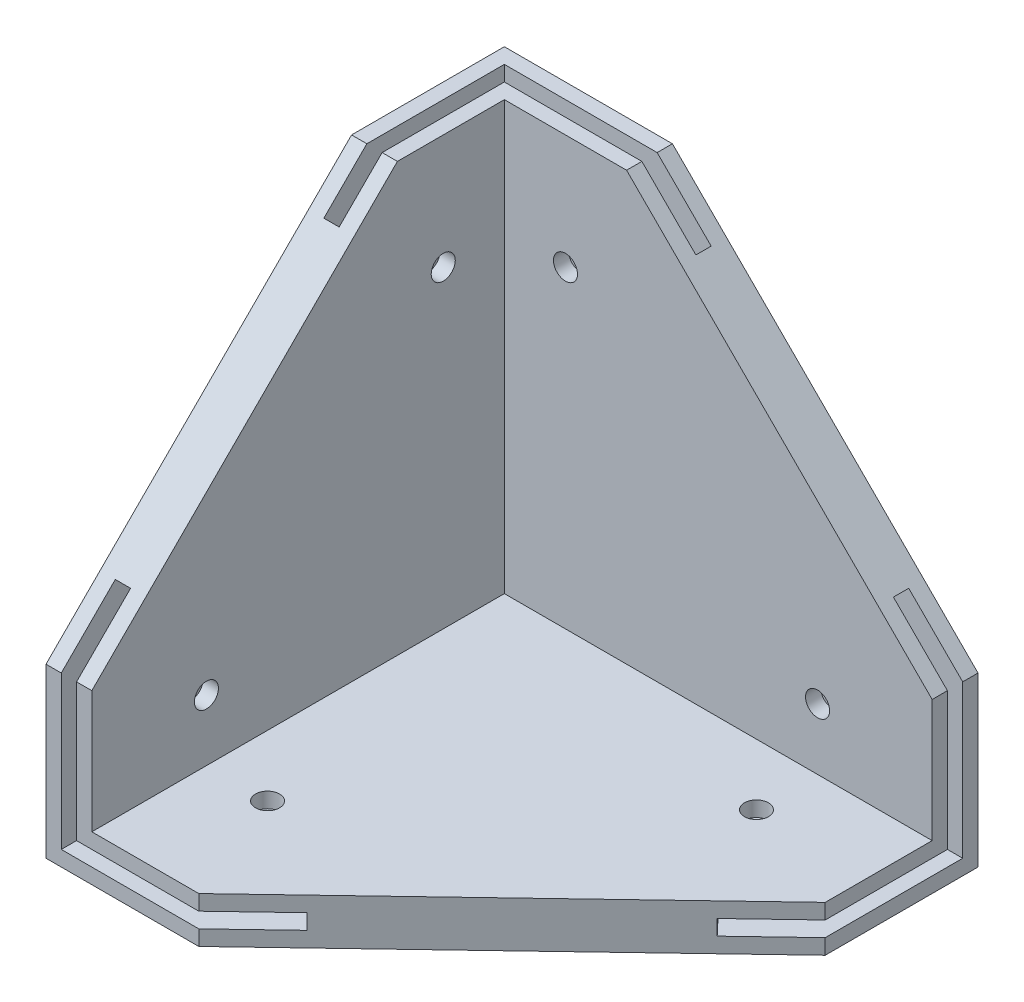
SolidWorks part; units mm, degrees
ref_plane "Front Plane" through (0, 0, 0) normal (0, 0, 1) x (1, 0, 0)
ref_plane "Top Plane" through (0, 0, 0) normal (0, 1, 0) x (1, 0, 0)
ref_plane "Right Plane" through (0, 0, 0) normal (1, 0, 0) x (0, 0, -1)
sketch "Sketch1" plane through (0, 0, 0) normal (0, 0, 1) x (1, 0, 0)
  line L0 (0, 76.2) -> (0, 0)
  line L1 (0, 0) -> (76.2, 0)
  line L2 (76.2, 0) -> (76.2, 25.4)
  line L3 (76.2, 25.4) -> (25.4, 76.2)
  line L4 (25.4, 76.2) -> (0, 76.2)
  dimension "D1" = 76.2
  dimension "D2" = 76.2
  dimension "D3" = 25.4
  dimension "D4" = 25.4
extrude "Boss-Extrude1" add sketch "Sketch1" along normal blind 2.54
sketch "Sketch3" plane through (0, 0, 0) normal (-1, 0, 0) x (0, 0, 1)
  line L0 (0, 76.2) -> (25.4, 76.2)
  line L2 (0, 76.2) -> (0, 0)
  line L3 (0, 0) -> (76.2, 0)
  line L4 (76.2, 0) -> (76.2, 25.4)
  line L6 (25.4, 76.2) -> (76.2, 25.4)
  dimension "D1" = 25.4
  dimension "D2" = 25.4
  dimension "D3" = 76.2
extrude "Boss-Extrude2" add sketch "Sketch3" along normal blind 2.54
sketch "Sketch5" plane through (0, 0, 0) normal (0, -1, 0) x (1, 0, 0)
  line L0 (-2.54, 76.2) -> (-2.54, 0)
  line L1 (-2.54, 0) -> (-2.54, 76.2) construction
  line L2 (-2.54, 0) -> (76.2, 0)
  line L3 (76.2, 0) -> (76.2, 25.4)
  line L4 (76.2, 25.4) -> (22.86, 76.2)
  line L5 (22.86, 76.2) -> (-2.54, 76.2)
  line L6 (-2.54, 76.2) -> (0, 76.2) construction
  dimension "D1" = 25.4
  dimension "D2" = 25.4
extrude "Boss-Extrude3" add sketch "Sketch5" along normal blind 2.54
sketch "Sketch6" plane through (0, 0, 0) normal (0, 0, 1) x (1, 0, 0)
  line L0 (22.86, 0) -> (0, 0) construction
  line L1 (2.54, 0) -> (5.08, 0)
  line L2 (2.54, 0) -> (2.54, 76.2)
  line L3 (2.54, 76.2) -> (5.08, 76.2)
  line L4 (5.08, 0) -> (5.08, 76.2)
  line L5 (25.4, 76.2) -> (0, 76.2) construction
  line L6 (0, 76.2) -> (0, 0) construction
  dimension "D1" = 2.54
  dimension "D2" = 2.54
extrude "Boss-Extrude4" add sketch "Sketch6" along direction (0, 0, -1) on the side of the normal blind 76.2
sketch "Sketch7" plane through (0, 0, 0) normal (1, 0, 0) x (0, 0, -1)
  line L0 (-25.4, 76.2) -> (-76.2, 25.4)
  line L1 (-76.2, 25.4) -> (-76.2, 76.2)
  line L2 (-76.2, 76.2) -> (-25.4, 76.2)
extrude "Cut-Extrude1" cut sketch "Sketch7" along normal up to next
sketch "Sketch8" plane through (0, 0, 0) normal (1, 0, 0) x (0, 0, -1)
  line L0 (-25.4, 76.2) -> (-2.54, 76.2) construction
  line L1 (-7.62, 76.2) -> (-5.08, 76.2)
  line L2 (-7.62, 76.2) -> (-7.62, -2.54)
  line L3 (-7.62, -2.54) -> (-5.08, -2.54)
  line L4 (-5.08, 76.2) -> (-5.08, -2.54)
  line L5 (0, -2.54) -> (-25.4, -2.54) construction
  line L6 (-2.54, 76.2) -> (-2.54, 0) construction
  dimension "D1" = 2.54
  dimension "D2" = 2.54
extrude "Boss-Extrude5" add sketch "Sketch8" along normal blind 76.2
sketch "Sketch9" plane through (0, 0, 0) normal (0, 0, 1) x (1, 0, 0)
  line L0 (76.2, 25.4) -> (25.4, 76.2)
  line L1 (25.4, 76.2) -> (76.2, 76.2)
  line L2 (76.2, 76.2) -> (76.2, 25.4)
extrude "Cut-Extrude2" cut sketch "Sketch9" along normal up to next
sketch "Sketch10" plane through (0, 0, 0) normal (0, 0, 1) x (1, 0, 0)
  line L0 (-2.54, -2.54) -> (-2.54, 25.4) construction
  line L1 (-2.54, 2.54) -> (76.2, 2.54)
  line L2 (-2.54, 2.54) -> (-2.54, 5.08)
  line L3 (-2.54, 5.08) -> (76.2, 5.08)
  line L4 (76.2, 2.54) -> (76.2, 5.08)
  line L5 (76.2, 25.4) -> (76.2, 0) construction
  line L6 (5.08, 0) -> (76.2, 0) construction
  dimension "D1" = 2.54
  dimension "D2" = 2.54
extrude "Boss-Extrude6" add sketch "Sketch10" along normal blind 76.2
sketch "Sketch11" plane through (0, 0, 0) normal (0, 1, 0) x (1, 0, 0)
  line L0 (22.86, -76.2) -> (76.2, -25.4)
  line L1 (76.2, -25.4) -> (76.2, -76.2)
  line L2 (76.2, -76.2) -> (22.86, -76.2)
extrude "Cut-Extrude3" cut sketch "Sketch11" along normal up to next
sketch "Sketch12" plane through (0, 0, 0) normal (1, 0, 0) x (0, 0, -1)
  line L0 (-5.08, 5.08) -> (-5.08, 2.54)
  line L1 (-5.08, 2.54) -> (-7.62, 2.54)
  line L2 (-7.62, 2.54) -> (-7.62, 0)
  line L3 (-7.62, 2.54) -> (-7.62, 0) construction
  line L4 (-7.62, 0) -> (-2.54, 0)
  line L5 (-2.54, 0) -> (-2.54, 5.08)
  line L6 (-2.54, 5.08) -> (-5.08, 5.08)
extrude "Cut-Extrude5" cut sketch "Sketch12" along normal through all
sketch "Sketch13" plane through (0, 0, 0) normal (0, 1, 0) x (1, 0, 0)
  line L0 (0, -2.54) -> (0, -7.62)
  line L1 (0, -7.62) -> (2.54, -7.62)
  line L2 (2.54, -7.62) -> (2.54, -5.08)
  line L3 (2.54, -5.08) -> (2.54, -2.54) construction
  line L4 (2.54, -5.08) -> (5.08, -5.08)
  line L5 (5.08, -5.08) -> (5.08, -2.54)
  line L6 (5.08, -2.54) -> (0, -2.54)
extrude "Cut-Extrude6" cut sketch "Sketch13" along normal through all
sketch "Sketch15" plane through (0, 0, 2.54) normal (0, 0, 1) x (1, 0, 0)
  line L0 (2.54, 5.08) -> (0, 5.08)
  line L1 (0, 5.08) -> (0, 0)
  line L2 (0, 0) -> (5.08, 0)
  line L3 (0, 0) -> (76.2, 0) construction
  line L4 (22.86, 0) -> (5.08, 0) construction
  line L5 (5.08, 0) -> (5.08, 2.54)
  line L6 (5.08, 0) -> (5.08, 2.54) construction
  line L7 (5.08, 2.54) -> (2.54, 2.54)
  line L8 (2.54, 2.54) -> (2.54, 5.08)
extrude "Cut-Extrude9" cut sketch "Sketch15" along normal blind 76.2
sketch "Sketch17" plane through (0, 0, 0) normal (0, 0, -1) x (-1, 0, 0)
  line L0 (-67.2197, 34.3803) -> (-34.3803, 67.2197)
  line L1 (-76.2, 25.4) -> (-25.4, 76.2) construction
  line L2 (-34.3803, 67.2197) -> (-30.7882, 63.6276)
  line L3 (-30.7882, 63.6276) -> (-63.6276, 30.7882)
  line L4 (-63.6276, 30.7882) -> (-67.2197, 34.3803)
  dimension "D1" = 12.7
  dimension "D2" = 12.7
  dimension "D3" = 5.08
extrude "Boss-Extrude7" add sketch "Sketch17" against normal up to surface (7.62 mm away) up to face at (37.592, 37.592, 7.62)
sketch "Sketch18" plane through (0, 0, 0) normal (0, 1, 0) x (1, 0, 0)
  line L0 (32.0566, -67.4414) -> (67.0034, -34.1586)
  line L1 (76.2, -25.4) -> (22.86, -76.2) construction
  line L2 (67.0034, -34.1586) -> (63.5, -30.48)
  line L3 (63.5, -30.48) -> (28.5531, -63.7628)
  line L4 (28.5531, -63.7628) -> (32.0566, -67.4414)
  dimension "D1" = 12.7
  dimension "D2" = 12.7
  dimension "D3" = 5.08
extrude "Boss-Extrude8" add sketch "Sketch18" along normal up to surface (5.08 mm away) up to face at (37.084, 5.08, 38.608)
sketch "Sketch19" plane through (0, 0, 0) normal (1, 0, 0) x (0, 0, -1)
  line L0 (-32.545, 69.055) -> (-67.2197, 34.3803)
  line L1 (-76.2, 25.4) -> (-25.4, 76.2) construction
  line L2 (-67.2197, 34.3803) -> (-63.6276, 30.7882)
  line L3 (-63.6276, 30.7882) -> (-28.9529, 65.4629)
  line L4 (-28.9529, 65.4629) -> (-32.545, 69.055)
  point P4 (-49.8824, 51.7176)
  dimension "D1" = 10.1046
  dimension "D2" = 12.7
  dimension "D3" = 5.08
extrude "Boss-Extrude9" add sketch "Sketch19" along normal up to surface (5.08 mm away) up to face at (5.08, 37.592, 38.608)
sketch "Sketch34" plane through (0, 0, 0) normal (1, 0, 0) x (0, 0, -1)
  line L0 (-17.78, 89.2211) -> (-17.78, -21.4288) construction
  line L1 (12.0246, 15.24) -> (-100.539, 15.24) construction
  line L2 (0, 76.2) -> (0, -2.54) construction
  line L3 (-76.2, -2.54) -> (0, -2.54) construction
  line L4 (19.1577, 57.15) -> (-54.087, 57.15) construction
  line L5 (19.1577, 29.21) -> (-54.087, 29.21) construction
  line L6 (-57.15, 27.3793) -> (-57.15, -35.5499) construction
  line L7 (-31.75, 27.3793) -> (-31.75, -35.5499) construction
  line L8 (-76.2, -2.54) -> (-76.2, 25.4) construction
  circle A0 centre (-17.78, 57.15) radius 2
  circle A3 centre (-57.15, 15.24) radius 2
  dimension "D7" = 4
  dimension "D10" = 4
  dimension "D1" = 17.78
  dimension "D2" = 17.78
  dimension "D3" = 19.05
  dimension "D4" = 31.75
  dimension "D5" = 31.75
  dimension "D6" = 19.05
extrude "Cut-Extrude11" cut sketch "Sketch34" against normal mid plane 25.4
sketch "Sketch35" plane through (0, 0, 0) normal (0, 1, 0) x (1, 0, 0)
  line L0 (15.24, -87.9891) -> (15.24, 14.1496) construction
  line L1 (-2.54, -76.2) -> (-2.54, 0) construction
  line L2 (-9.517, -17.78) -> (98.4386, -17.78) construction
  line L3 (-2.54, 0) -> (76.2, 0) construction
  line L4 (-9.517, -57.15) -> (98.4386, -57.15) construction
  line L5 (22.86, -76.2) -> (-2.54, -76.2) construction
  line L6 (-9.517, -31.75) -> (98.4386, -31.75) construction
  line L7 (57.15, 14.1496) -> (57.15, -87.9891) construction
  line L8 (57.15, -87.9891) -> (57.15, 14.1496) construction
  line L9 (29.21, -87.9891) -> (29.21, 14.1496) construction
  line L10 (76.2, 0) -> (76.2, -25.4) construction
  circle A0 centre (15.24, -57.15) radius 2
  circle A3 centre (57.15, -17.78) radius 2
  dimension "D7" = 4
  dimension "D10" = 4
  dimension "D1" = 17.78
  dimension "D2" = 17.78
  dimension "D3" = 19.05
  dimension "D4" = 31.75
  dimension "D5" = 31.75
  dimension "D6" = 19.05
extrude "Cut-Extrude13" cut sketch "Sketch35" against normal mid plane 25.4
sketch "Sketch36" plane through (0, 0, 0) normal (0, 0, 1) x (1, 0, 0)
  line L0 (110.2526, 15.24) -> (-20.6631, 15.24) construction
  line L1 (15.24, 92.1582) -> (15.24, -15.0496) construction
  line L2 (-2.54, 76.2) -> (-2.54, -2.54) construction
  line L3 (-2.54, -2.54) -> (76.2, -2.54) construction
  line L4 (57.15, 92.1582) -> (57.15, -15.0496) construction
  line L5 (29.21, 92.1582) -> (29.21, -15.0496) construction
  line L6 (-20.6631, 29.21) -> (46.0631, 29.21) construction
  line L7 (-20.6631, 57.15) -> (110.2526, 57.15) construction
  line L8 (25.4, 76.2) -> (-2.54, 76.2) construction
  line L9 (76.2, -2.54) -> (76.2, 25.4) construction
  circle A0 centre (57.15, 15.24) radius 2
  circle A3 centre (15.24, 57.15) radius 2
  dimension "D7" = 4
  dimension "D10" = 4
  dimension "D1" = 17.78
  dimension "D2" = 17.78
  dimension "D3" = 19.05
  dimension "D4" = 31.75
  dimension "D5" = 19.05
  dimension "D6" = 31.75
extrude "Cut-Extrude14" cut sketch "Sketch36" against normal mid plane 25.4
sketch "Sketch37" plane through (0, 0, 0) normal (0, 0, 1) x (1, 0, 0)
  line L1 (0, 0) -> (25.4, 0)
  line L2 (0, 0) -> (0, 25.4)
  line L3 (0, 25.4) -> (25.4, 25.4)
  line L4 (25.4, 0) -> (25.4, 25.4)
  dimension "D1" = 25.4
  dimension "D2" = 25.4
extrude "Boss-Extrude10" add sketch "Sketch37" along normal up to surface (7.62 mm away) up to face at (57.15, 17.24, 7.62)
sketch "Sketch38" plane through (0, 0, 0) normal (0, 1, 0) x (1, 0, 0)
  line L0 (-2.54, -76.2) -> (-2.54, 0) construction
  line L1 (0, -2.54) -> (25.4, -2.54)
  line L2 (0, -2.54) -> (0, -27.94)
  line L3 (0, -27.94) -> (25.4, -27.94)
  line L4 (25.4, -2.54) -> (25.4, -27.94)
  line L5 (-2.54, 0) -> (76.2, 0) construction
  dimension "D1" = 2.54
  dimension "D2" = 2.54
  dimension "D3" = 25.4
  dimension "D4" = 25.4
extrude "Boss-Extrude11" add sketch "Sketch38" along normal up to surface (5.08 mm away) up to face at (15.24, 5.08, 55.15)
sketch "Sketch39" plane through (0, 0, 0) normal (1, 0, 0) x (0, 0, -1)
  line L0 (0, 76.2) -> (0, -2.54) construction
  line L1 (-2.54, 0) -> (-27.94, 0)
  line L2 (-2.54, 0) -> (-2.54, 25.4)
  line L3 (-2.54, 25.4) -> (-27.94, 25.4)
  line L4 (-27.94, 0) -> (-27.94, 25.4)
  line L5 (-76.2, -2.54) -> (0, -2.54) construction
  dimension "D1" = 2.54
  dimension "D2" = 2.54
  dimension "D3" = 25.4
  dimension "D4" = 25.4
extrude "Boss-Extrude12" add sketch "Sketch39" along normal up to surface (5.08 mm away) up to face at (5.08, 57.15, 19.78)
